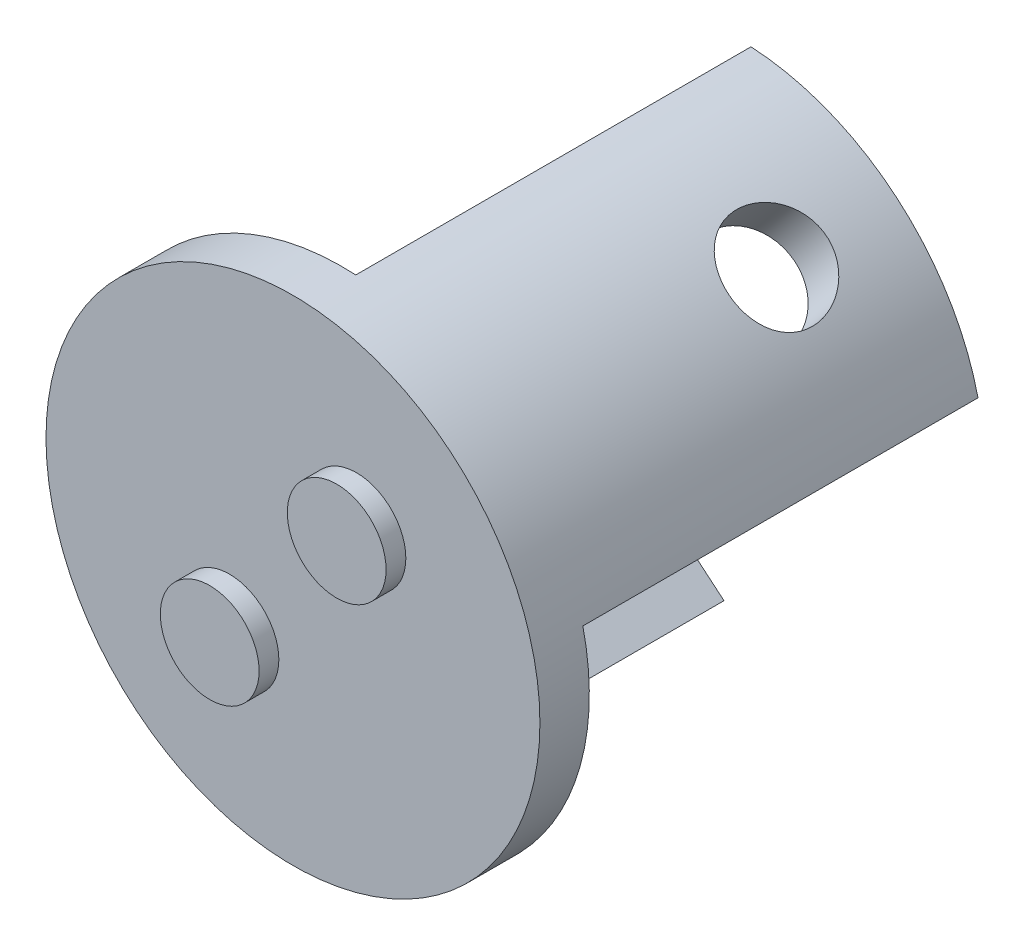
SolidWorks part; units mm, degrees
ref_plane "Front Plane" through (0, 0, 0) normal (0, 0, 1) x (1, 0, 0)
ref_plane "Top Plane" through (0, 0, 0) normal (0, 1, 0) x (1, 0, 0)
ref_plane "Right Plane" through (0, 0, 0) normal (1, 0, 0) x (0, 0, -1)
sketch "Sketch1" plane through (0, 0, 0) normal (0, 0, 1) x (1, 0, 0)
  circle A0 centre (0, 0) radius 25
  dimension "D1" = 50
extrude "Boss-Extrude1" add sketch "Sketch1" along normal blind 5
sketch "Sketch2" plane through (0, 0, 5) normal (0, 0, 1) x (1, 0, 0)
  line L0 (0, 0) -> (63.1489, 0) construction
  line L1 (0, 0) -> (36.9706, -31.022) construction
  line L2 (-23.9802, 7.0677) -> (11.1244, -22.3886)
  circle A0 centre (0, 0) radius 25 construction
  circle A1 centre (-6.4279, -7.6604) radius 5
  circle A2 centre (6.4279, 7.6604) radius 5
  dimension "D3" = 10
  dimension "D1" = 40
  dimension "D2" = 10
extrude "Boss-Extrude2" add sketch "Sketch2" along normal blind 2 contours L2 A1 | L2 A1 | A2
sketch "Sketch3" plane through (0, 0, 0) normal (0, 0, -1) x (-1, 0, 0)
  line L0 (0, 0) -> (-37.4207, 0) construction
  line L1 (0, 0) -> (-35.7569, -30.0036) construction
  line L2 (24.3464, -5.6791) -> (1.3651, -24.9627)
  line L3 (-1.3651, 24.9627) -> (-24.3464, 5.6791)
  circle A0 centre (0, 0) radius 20 construction
  circle A1 centre (0, 0) radius 25 construction
  circle A2 centre (0, 0) radius 25 construction
  arc A3 (-1.3651, 24.9627) -> (-25, 0) centre (0, 0) ccw
  arc A4 (1.3651, -24.9627) -> (24.3464, -5.6791) centre (0, 0) ccw
  circle M7 centre (0, 0) radius 25
  dimension "D1" = 40
  dimension "D2" = 40
  dimension "D3" = 20
extrude "Boss-Extrude3" add sketch "Sketch3" along normal blind 40 contours L3 M7 | L2 M7
sketch "Sketch6" plane through (12.8558, 15.3209, 0) normal (-0.6428, -0.766, 0) x (0.766, -0.6428, 0)
  line L0 (0, 7) -> (0, -28) construction
  line L1 (5, 7) -> (-5, 7) construction
  circle A0 centre (0, -28) radius 5
  dimension "D1" = 10
  dimension "D2" = 35
extrude "Cut-Extrude1" cut sketch "Sketch6" against normal through all both and the other way through all
